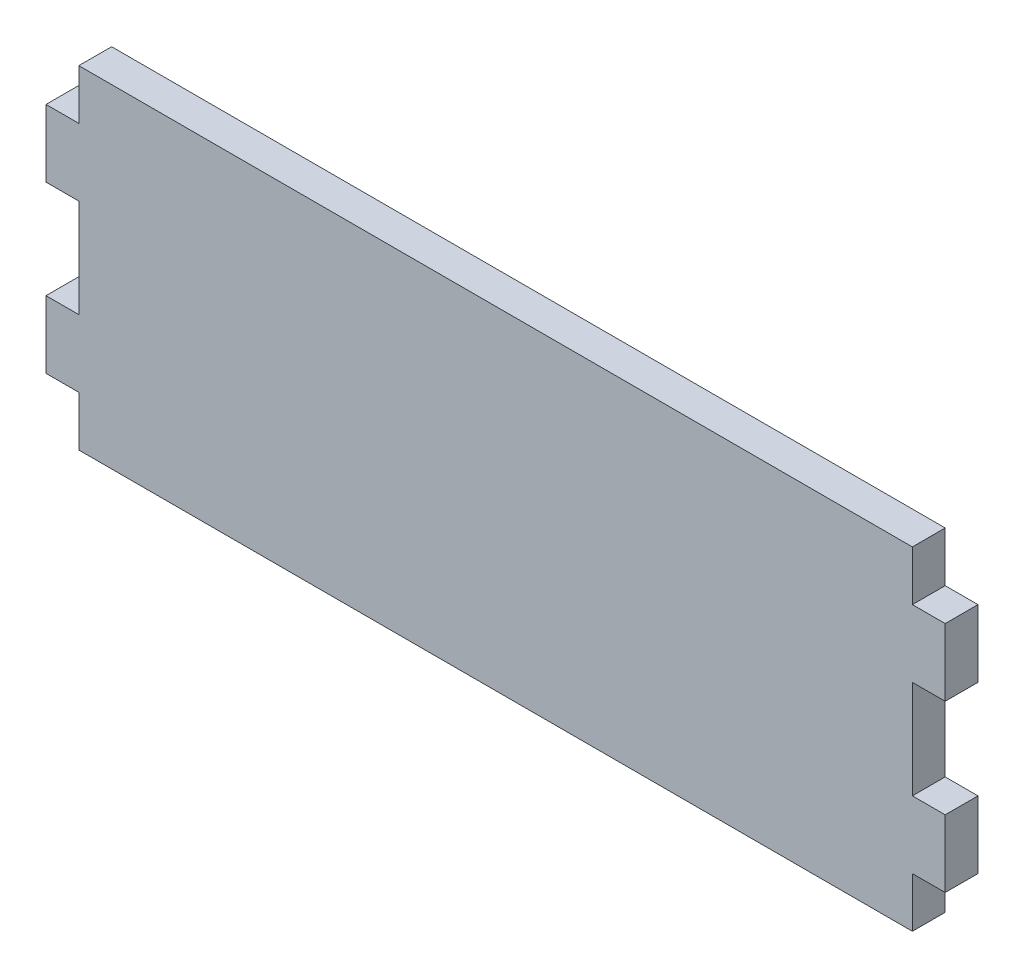
SolidWorks part; units mm, degrees
ref_plane "Front Plane" through (0, 0, 0) normal (0, 0, 1) x (1, 0, 0)
ref_plane "Top Plane" through (0, 0, 0) normal (0, 1, 0) x (1, 0, 0)
ref_plane "Right Plane" through (0, 0, 0) normal (1, 0, 0) x (0, 0, -1)
sketch "Sketch1" plane through (0, 0, 0) normal (0, 0, 1) x (1, 0, 0)
  line L0 (-63.5, 0.08) -> (-63.5, 50.72) construction
  line L1 (68.5, 0) -> (63.5, 0) construction
  line L2 (-63.5, 0.08) -> (-63.5, 50.72) construction
  line L3 (68.5, 0) -> (63.5, 0) construction
  line L5 (-63.5, 50.72) -> (63.5, 50.72)
  line L6 (-63.5, 50.72) -> (-63.5, 0)
  line L7 (-63.5, 0) -> (63.5, 0)
  line L8 (63.5, 50.72) -> (63.5, 0)
extrude "Boss-Extrude1" add sketch "Sketch1" against normal blind 5
sketch "Sketch2" plane through (0, 0, -5) normal (0, 0, -1) x (-1, 0, 0)
  line L0 (-63.5, 25.36) -> (63.5, 25.36) construction
  line L1 (-63.5, 0) -> (-63.5, 50.72) construction
  line L2 (63.5, 50.72) -> (63.5, 0) construction
  line L3 (0, 0) -> (0, 50.72) construction
  line L4 (63.5, 0) -> (-63.5, 0) construction
  line L5 (-63.5, 50.72) -> (63.5, 50.72) construction
  line L6 (-68.5, 7.6157) -> (-68.5, 17.8705)
  line L7 (-63.5, 43.1043) -> (-68.5, 43.1043)
  line L8 (-63.5, 43.1043) -> (-63.5, 32.8495)
  line L9 (-63.5, 32.8495) -> (-68.5, 32.8495)
  line L10 (-68.5, 43.1043) -> (-68.5, 32.8495)
  line L11 (-63.5, 7.6157) -> (-63.5, 17.8705)
  line L12 (-63.5, 7.6157) -> (-68.5, 7.6157)
  line L13 (-63.5, 17.8705) -> (-68.5, 17.8705)
  line L14 (63.5, 17.8705) -> (68.5, 17.8705)
  line L15 (63.5, 7.6157) -> (68.5, 7.6157)
  line L16 (63.5, 7.6157) -> (63.5, 17.8705)
  line L17 (68.5, 43.1043) -> (68.5, 32.8495)
  line L18 (63.5, 32.8495) -> (68.5, 32.8495)
  line L19 (63.5, 43.1043) -> (63.5, 32.8495)
  line L20 (63.5, 43.1043) -> (68.5, 43.1043)
  line L21 (68.5, 7.6157) -> (68.5, 17.8705)
  dimension "D1" = 5
extrude "Boss-Extrude2" add sketch "Sketch2" against normal up to surface (5 mm away) up to face at (0, 25.36, 0)
